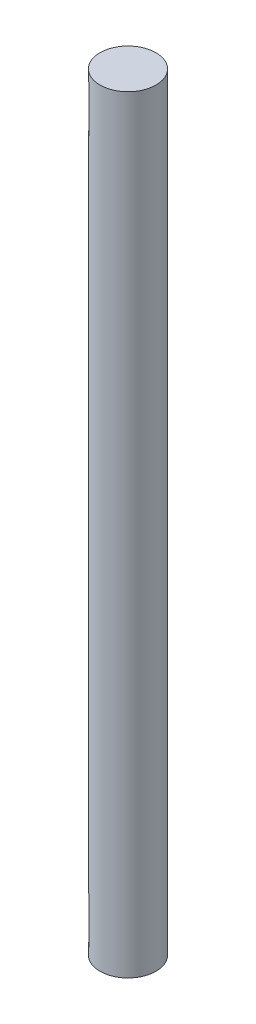
SolidWorks part; units mm, degrees
ref_plane "Piano frontale" through (0, 0, 0) normal (0, 0, 1) x (1, 0, 0)
ref_plane "Piano superiore" through (0, 0, 0) normal (0, 1, 0) x (1, 0, 0)
ref_plane "Piano destro" through (0, 0, 0) normal (1, 0, 0) x (0, 0, -1)
sketch "Schizzo2" plane through (0, 0, 0) normal (0, 1, 0) x (1, 0, 0)
  circle A0 centre (0, 0) radius 2.485
  dimension "D1" = 4.97
extrude "Estrusione-Estrusione1" add sketch "Schizzo2" along normal blind 68.1
sketch "Schizzo3" plane through (0, 0, 0) normal (0, 0, 1) x (1, 0, 0)
  line L0 (-2.485, 68.1) -> (-2.485, 0) construction
  line L1 (-2.485, 67.31) -> (-1.435, 67.31)
  line L2 (-2.485, 67.31) -> (-2.485, 63.15)
  line L3 (-2.485, 63.15) -> (-1.435, 63.15)
  line L4 (-1.435, 67.31) -> (-1.435, 63.15)
  line L5 (-2.485, 34.05) -> (2.485, 34.05) construction
  line L6 (2.485, 0) -> (2.485, 68.1) construction
  line L7 (-1.435, 0.79) -> (-1.435, 4.95)
  line L8 (-2.485, 4.95) -> (-1.435, 4.95)
  line L9 (-2.485, 0.79) -> (-2.485, 4.95)
  line L10 (-2.485, 0.79) -> (-1.435, 0.79)
  dimension "D1" = 4.16
  dimension "D2" = 58.2
  dimension "D3" = 1.05
extrude "Taglio-Estrusione1" cut sketch "Schizzo3" against normal through all and the other way through all
